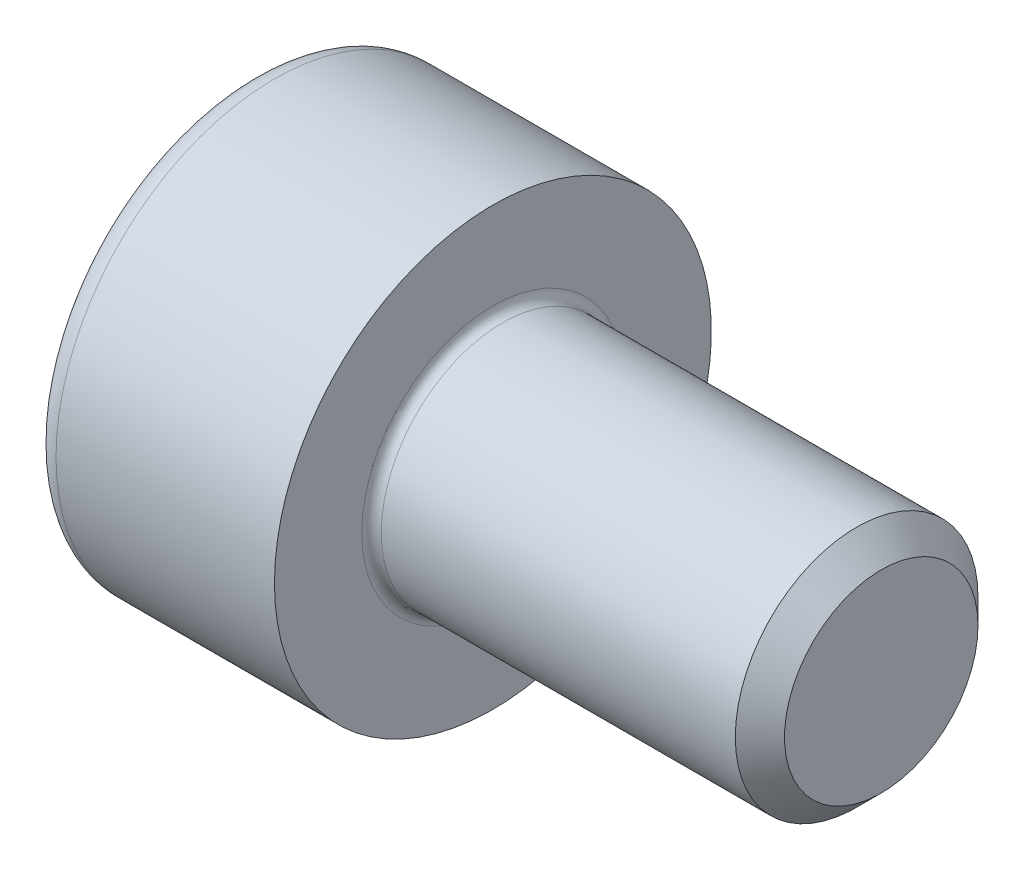
SolidWorks part; units mm, degrees
ref_plane "Спереди" through (0, 0, 0) normal (0, 0, 1) x (1, 0, 0)
ref_plane "Сверху" through (0, 0, 0) normal (0, 1, 0) x (1, 0, 0)
ref_plane "Справа" through (0, 0, 0) normal (1, 0, 0) x (0, 0, -1)
ref_plane "Плоскость4" through (0, 0, 0) normal (0, 0, -1) x (-1, 0, 0)
sketch "Эскиз1" plane through (0, 0, 0) normal (0, 0, -1) x (-1, 0, 0)
  line L0 (-2.5, 2.25) -> (-2.5, 0)
  line L1 (-2.5, 0) -> (0, 0)
  line L2 (0, 0) -> (0, 2.25)
  line L3 (0, 2.25) -> (-2.5, 2.25)
  line L4 (-2.5, 0) -> (0, 0) construction
revolve "Повернуть1" add sketch "Эскиз1" angle 360 about L4
sketch "Эскиз2" plane through (2.5, 0, 0) normal (1, 0, 0) x (0, 0, -1)
  circle A0 centre (0, 0) radius 1.25
extrude "Бобышка-Вытянуть1" add sketch "Эскиз2" along normal blind 4
sketch "Эскиз3" plane through (0, 0, 0) normal (-1, 0, 0) x (0, 0, 1)
  line L0 (-1.01, -0.5831) -> (0, -1.1662)
  line L1 (0, -1.1662) -> (1.01, -0.5831)
  line L2 (1.01, -0.5831) -> (1.01, 0.5831)
  line L3 (1.01, 0.5831) -> (0, 1.1662)
  line L4 (0, 1.1662) -> (-1.01, 0.5831)
  line L5 (-1.01, 0.5831) -> (-1.01, -0.5831)
extrude "Вырез-Вытянуть1" cut sketch "Эскиз3" against normal blind 1.1
sketch "Эскиз4" plane through (0, 0, 0) normal (0, 0, 1) x (1, 0, 0)
  line L0 (1.1, 1.01) -> (1.1, 0)
  line L1 (1.1, 0) -> (1.6831, 0)
  line L2 (1.6831, 0) -> (1.1, 1.01)
  line L3 (1.1, 0) -> (1.6832, 0) construction
revolve "Вырез-Повернуть1" cut sketch "Эскиз4" angle 360 about L3
chamfer "Фаска1" distance 0.2535 angle 45 1 edges at (6.5, 0, -1.25)
fillet "Скругление1" radius 0.1 1 edges at (2.5, 0, -1.25)
fillet "Скругление2" radius 0.25 1 edges at (0, 0, 2.25)
